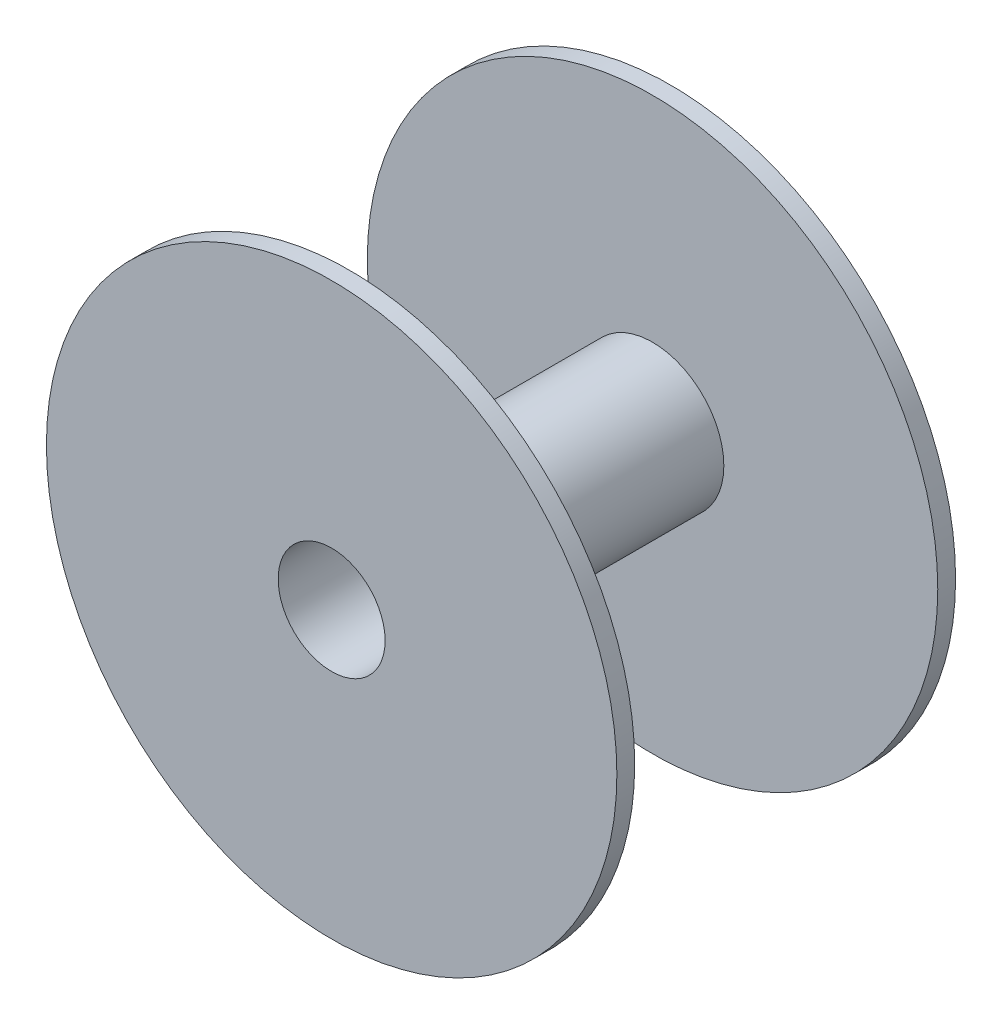
SolidWorks part; units mm, degrees
ref_plane "Front Plane" through (0, 0, 0) normal (0, 0, 1) x (1, 0, 0)
ref_plane "Top Plane" through (0, 0, 0) normal (0, 1, 0) x (1, 0, 0)
ref_plane "Right Plane" through (0, 0, 0) normal (1, 0, 0) x (0, 0, -1)
sketch "Sketch1" plane through (0, 0, 0) normal (0, 0, 1) x (1, 0, 0)
  circle A0 centre (0, 0) radius 80
  circle A1 centre (0, 0) radius 15
  dimension "D1" = 30
  dimension "D2" = 160
extrude "Boss-Extrude1" add sketch "Sketch1" along normal blind 95
shell "Shell1" thickness 5
